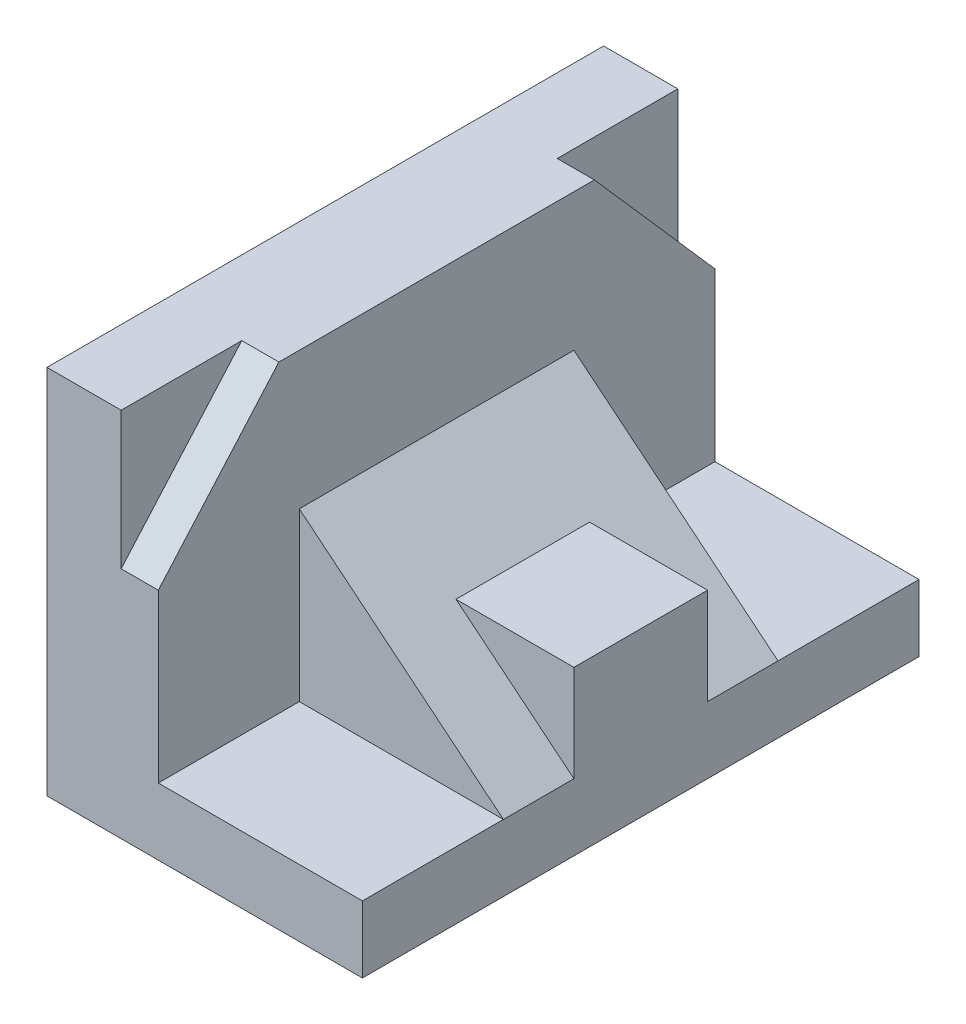
SolidWorks part; units mm, degrees
ref_plane "Front Plane" through (0, 0, 0) normal (0, 0, 1) x (1, 0, 0)
ref_plane "Top Plane" through (0, 0, 0) normal (0, 1, 0) x (1, 0, 0)
ref_plane "Right Plane" through (0, 0, 0) normal (1, 0, 0) x (0, 0, -1)
sketch "Sketch1" plane through (0, 0, 0) normal (0, 1, 0) x (1, 0, 0)
  line L1 (-39.0656, 120.3092) -> (45.9344, 120.3092)
  line L2 (-39.0656, 120.3092) -> (-39.0656, -29.6908)
  line L3 (-39.0656, -29.6908) -> (45.9344, -29.6908)
  line L4 (45.9344, 120.3092) -> (45.9344, -29.6908)
  dimension "D1" = 85
  dimension "D2" = 150
extrude "Boss-Extrude1" add sketch "Sketch1" along normal blind 18
sketch "Sketch2" plane through (0, 18, 0) normal (0, 1, 0) x (1, 0, 0)
  line L0 (-39.0656, 120.3092) -> (-39.0656, -29.6908) construction
  line L1 (-39.0656, 120.3092) -> (-9.0656, 120.3092)
  line L2 (-39.0656, 120.3092) -> (-39.0656, -29.6908)
  line L3 (-39.0656, -29.6908) -> (-9.0656, -29.6908)
  line L4 (-9.0656, 120.3092) -> (-9.0656, -29.6908)
  point P6 (-39.0656, 45.3092)
  point P7 (-39.0656, 45.3092)
  dimension "D1" = 150
  dimension "D2" = 30
extrude "Boss-Extrude2" add sketch "Sketch2" along normal offset from surface (82 mm away) 100 up to face at (3.4344, 0, -45.3092)
sketch "Sketch3" plane through (0, 18, 0) normal (0, 1, 0) x (1, 0, 0)
  line L0 (45.9344, -29.6908) -> (45.9344, 120.3092) construction
  line L1 (-9.0656, 82.3092) -> (45.9344, 82.3092)
  line L2 (-9.0656, 82.3092) -> (-9.0656, 8.3092)
  line L3 (-9.0656, 8.3092) -> (45.9344, 8.3092)
  line L4 (45.9344, 82.3092) -> (45.9344, 8.3092)
  line L5 (-9.0656, -29.6908) -> (-9.0656, 120.3092) construction
  point P6 (45.9344, 45.3092)
  point P7 (45.9344, 45.3092)
  point P10 (-9.0656, 45.3092)
  point P11 (-9.0656, 45.3092)
  dimension "D1" = 74
extrude "Boss-Extrude3" add sketch "Sketch3" along normal blind 45
sketch "Sketch4" plane through (0, 0, -8.3092) normal (0, 0, 1) x (1, 0, 0)
  line L0 (45.9344, 18) -> (-9.0656, 63)
  line L1 (-9.0656, 63) -> (-9.0656, 18) construction
  line L2 (-9.0656, 63) -> (45.9344, 63) construction
  line L3 (-9.0656, 63) -> (45.9344, 63)
  line L4 (45.9344, 63) -> (45.9344, 18)
extrude "Cut-Extrude1" cut sketch "Sketch4" against normal blind 74
sketch "Sketch5" plane through (0, 18, 0) normal (0, 1, 0) x (1, 0, 0)
  line L0 (45.9344, 82.3092) -> (45.9344, 8.3092) construction
  line L1 (-39.0656, 63.3092) -> (45.9344, 63.3092)
  line L2 (-39.0656, 63.3092) -> (-39.0656, 27.3092)
  line L3 (-39.0656, 27.3092) -> (45.9344, 27.3092)
  line L4 (45.9344, 63.3092) -> (45.9344, 27.3092)
  point P6 (45.9344, 45.3092)
  point P7 (45.9344, 45.3092)
  dimension "D1" = 36
  dimension "D2" = 85
extrude "Boss-Extrude4" add sketch "Sketch5" along normal offset from surface (26 mm away) 44 up to face at (3.4344, 0, -45.3092)
sketch "Sketch7" plane through (-9.0656, 0, 0) normal (1, 0, 0) x (0, 0, -1)
  line L0 (-29.6908, 100) -> (120.3092, 100) construction
  line L1 (-29.6908, 100) -> (120.3092, 100)
  line L2 (-29.6908, 100) -> (-29.6908, 63)
  line L3 (-29.6908, 63) -> (120.3092, 63)
  line L4 (120.3092, 100) -> (120.3092, 63)
  point P6 (45.3092, 100)
  point P7 (45.3092, 100)
  dimension "D1" = 150
  dimension "D2" = 37
extrude "Cut-Extrude2" cut sketch "Sketch7" against normal blind 10
sketch "Sketch8" plane through (-19.0656, 0, 0) normal (1, 0, 0) x (0, 0, -1)
  line L0 (2.8092, 100) -> (87.8092, 100)
  line L1 (-29.6908, 63) -> (120.3092, 63)
  line L2 (120.3092, 100) -> (-29.6908, 100) construction
  line L3 (-29.6908, 63) -> (120.3092, 63) construction
  line L4 (2.8092, 100) -> (-29.6908, 63)
  line L5 (87.8092, 100) -> (120.3092, 63)
  point P6 (45.3092, 100)
  point P7 (45.3092, 100)
  point P10 (45.3092, 63)
  point P11 (45.3092, 63)
  dimension "D1" = 150
  dimension "D2" = 85
extrude "Boss-Extrude5" add sketch "Sketch8" along normal blind 10
